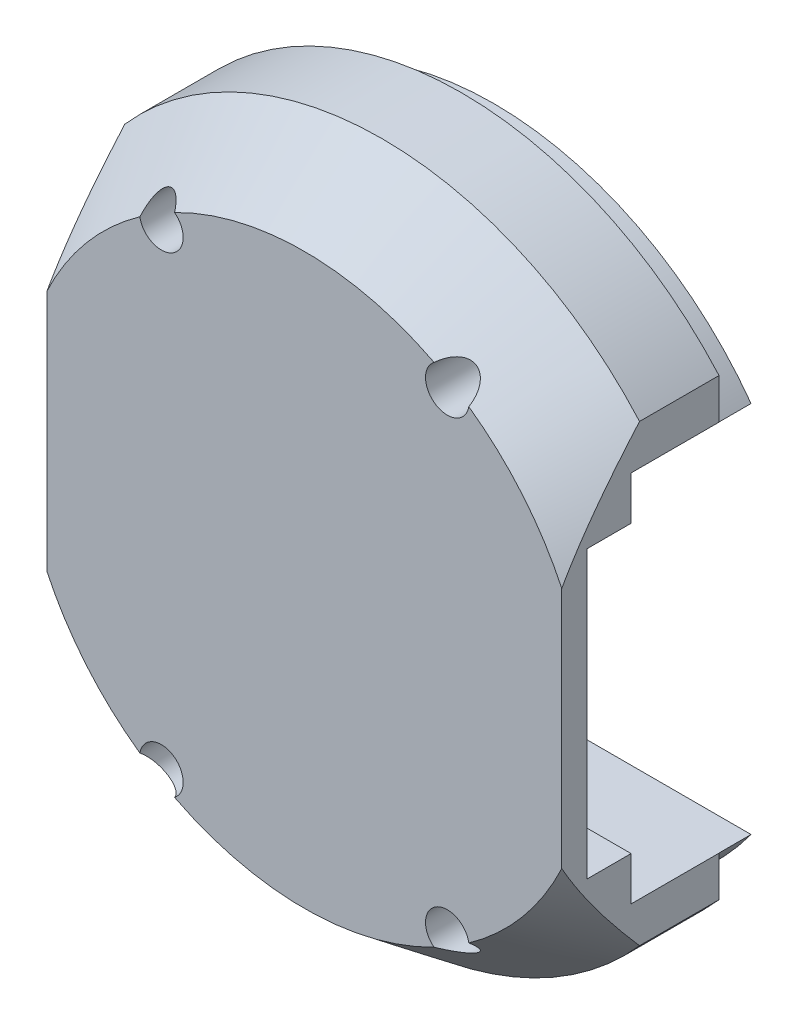
SolidWorks part; units mm, degrees
ref_plane "Front Plane" through (0, 0, 0) normal (0, 0, 1) x (1, 0, 0)
ref_plane "Top Plane" through (0, 0, 0) normal (0, 1, 0) x (1, 0, 0)
ref_plane "Right Plane" through (0, 0, 0) normal (1, 0, 0) x (0, 0, -1)
sketch "Sketch1" plane through (0, 0, 0) normal (0, 0, 1) x (1, 0, 0)
  line L1 (-18.8872, 0) -> (15.5738, 0) construction
  arc A0 (-22.225, -0.0261) -> (22.225, 0) centre (0, 0) ccw
  arc A1 (-22.225, -0.0261) -> (22.225, 0) centre (0, 0) cw
  dimension "D1" = 44.45
extrude "Extrude1" add sketch "Sketch1" along normal blind 2.25
sketch "Sketch2" plane through (0, 0, 2.25) normal (0, 0, 1) x (1, 0, 0)
  line L1 (-19.1115, 0) -> (18.219, 0) construction
  arc A0 (-23.9999, -0.0783) -> (23.9995, 0.1489) centre (0, 0) ccw
  arc A1 (-23.9999, -0.0783) -> (23.9995, 0.1489) centre (0, 0) cw
  dimension "D1" = 48
extrude "Extrude2" add sketch "Sketch2" along normal blind 11
chamfer "Chamfer1" distance 4.1 angle 53 1 edges at (-24, 0, 13.25)
sketch "Sketch6" plane through (0, 0, 0) normal (0, 0, -1) x (-1, 0, 0)
  line L0 (-30, 13.05) -> (30, 13.05)
  line L1 (-30, -13.05) -> (30, -13.05)
  line L2 (-30, -13.05) -> (-30, 13.05)
  line L3 (-30, 0) -> (30, 0) construction
  line L4 (30, -13.05) -> (30, 13.05)
  dimension "D2" = 30
  dimension "D3" = 30
  dimension "D1" = 13.05
extrude "Cut-Extrude1" cut sketch "Sketch6" against normal blind 8.4
sketch "Sketch9" plane through (0, 0, 0) normal (0, 0, -1) x (-1, 0, 0)
  line L1 (-28, -20) -> (-18, -20)
  line L2 (-28, -20) -> (-28, 20)
  line L3 (-28, 20) -> (-18, 20)
  line L4 (-18, -20) -> (-18, 20)
  line L5 (0, 0) -> (0, -27.3159) construction
  line L6 (18, -20) -> (18, 20)
  line L7 (28, 20) -> (18, 20)
  line L8 (28, -20) -> (28, 20)
  line L9 (28, -20) -> (18, -20)
  line L10 (0, 0) -> (18, 0) construction
  dimension "D1" = 40
  dimension "D2" = 18
  dimension "D3" = 10
extrude "Cut-Extrude3" cut sketch "Sketch9" against normal through all
sketch "Sketch10" plane through (0, 0, 8.4) normal (0, 0, -1) x (-1, 0, 0)
  line L1 (22, 10) -> (-22, 10)
  line L2 (22, 10) -> (22, -10)
  line L3 (22, -10) -> (-22, -10)
  line L4 (-22, 10) -> (-22, -10)
  dimension "D1" = 10
  dimension "D2" = 10
  dimension "D3" = 22
  dimension "D4" = 22
extrude "Cut-Extrude4" cut sketch "Sketch10" against normal blind 3.1
sketch "Sketch11" plane through (0, 0, 13.25) normal (0, 0, 1) x (1, 0, 0)
  circle A0 centre (0, 0) radius 6
  dimension "D1" = 12
extrude "Extrude3" [suppressed] add sketch "Sketch11" along normal blind 4.8
sketch "Sketch12" [suppressed] plane through (0, 0, 19.05) normal (0, 0, 1) x (1, 0, 0)
  circle A0 centre (0, 0) radius 2.275
  dimension "D1" = 4.55
extrude "Cut-Extrude5" [suppressed] cut sketch "Sketch12" against normal through all
chamfer "Chamfer2" [suppressed] distance 4 angle 45
sketch "Sketch13" [suppressed] plane through (0, 0, 14.25) normal (0, 0, 1) x (1, 0, 0)
  line L0 (0, 0) -> (0, 33.8431) construction
  line L1 (0, 0) -> (21.9948, 0) construction
  circle A0 centre (10, 16.5) radius 2.5
  circle A1 centre (-10, 16.5) radius 2.5
  circle A2 centre (-10, -16.5) radius 2.5
  circle A3 centre (10, -16.5) radius 2.5
  dimension "D3" = 5
  dimension "D1" = 10
  dimension "D2" = 16.5
extrude "Cut-Extrude6" [suppressed] cut sketch "Sketch13" against normal blind 5
sketch "Sketch14" [suppressed] plane through (0, 0, 9.25) normal (0, 0, 1) x (1, 0, 0)
  line L0 (0, 0) -> (16.3574, 0) construction
  line L1 (0, 0) -> (0, 20.9629) construction
  circle A0 centre (10, 16.5) radius 1.15
  circle A1 centre (-10, 16.5) radius 1.15
  circle A2 centre (-10, -16.5) radius 1.15
  circle A3 centre (10, -16.5) radius 1.15
  dimension "D1" = 2.3
extrude "Cut-Extrude7" [suppressed] cut sketch "Sketch14" against normal through all
sketch "Sketch15" plane through (0, 0, 0) normal (0, 0, -1) x (-1, 0, 0)
  line L0 (0, 0) -> (22.4929, 0) construction
  line L1 (0, 0) -> (0, 30.0852) construction
  line L2 (6, -13) -> (6, 13)
  line L3 (-6, -13) -> (-6, 13)
  line L4 (0, 0) -> (-14.6849, 0) construction
  arc A0 (6, 13) -> (-6, 13) centre (0, 13) ccw
  arc A1 (6, -13) -> (-6, -13) centre (0, -13) cw
  point P3 (-6, 0)
  point P13 (6, 0)
  dimension "D1" = 13
  dimension "D2" = 6
extrude "Cut-Extrude8" cut sketch "Sketch15" against normal up to surface (11.5 mm away) up to face at (0, 0, 11.5)
sketch "Sketch16" plane through (0, 0, 0) normal (0, 0, -1) x (-1, 0, 0)
  line L0 (0, 0) -> (-26.9468, 0) construction
  line L1 (0, 0) -> (0, -31.7311) construction
  circle A0 centre (-10, -16.5) radius 1.525
  circle A1 centre (10, -16.5) radius 1.525
  circle A2 centre (10, 16.5) radius 1.525
  circle A3 centre (-10, 16.5) radius 1.525
  dimension "D1" = 3.05
  dimension "D2" = 16.5
  dimension "D3" = 10
extrude "Cut-Extrude9" cut sketch "Sketch16" against normal through all
sketch "Sketch17" plane through (0, 0, 13.25) normal (0, 0, 1) x (1, 0, 0)
  circle A0 centre (0, 0) radius 2.275
  dimension "D1" = 4.55
extrude "Cut-Extrude10" [suppressed] cut sketch "Sketch17" against normal through all
sketch "Sketch18" [suppressed] plane through (0, 0, 14.25) normal (0, 0, 1) x (1, 0, 0)
  circle A0 centre (0, 0) radius 2.275 construction
  circle A1 centre (0, 0) radius 2.275
  circle A2 centre (0, 0) radius 3.05
  dimension "D1" = 6.1
extrude "Extrude4" [suppressed] add sketch "Sketch18" along normal blind 0.3
chamfer "Chamfer3" [suppressed] distance 0.7 angle 45
fillet "Fillet1" [suppressed] radius 1.2
sketch "Sketch19" [suppressed] plane through (0, 0, 13) normal (0, 0, -1) x (-1, 0, 0)
  line L1 (4, 7) -> (-4, 7)
  line L2 (4, -7) -> (-4, -7)
  line L3 (-4, 13) -> (-4, -13)
  line L4 (4, -13) -> (4, 13)
  line L6 (0, 0) -> (13.3401, 0) construction
  line L7 (-4, 13) -> (-4, 7)
  line L8 (4, -13) -> (4, -7)
  line L9 (4, 7) -> (4, 13)
  line L10 (-4, -7) -> (-4, -13)
  arc A3 (4, 13) -> (-4, 13) centre (0, 13) ccw
  arc A4 (-4, -13) -> (4, -13) centre (0, -13) ccw
  arc A5 (4, 13) -> (-4, 13) centre (0, 13) ccw
  arc A6 (-4, -13) -> (4, -13) centre (0, -13) ccw
  dimension "D1" = 0
  dimension "D2" = 7
extrude "Cut-Extrude11" [suppressed] cut sketch "Sketch19" against normal through all
sketch "Sketch20" [suppressed] plane through (0, 0, 8.4) normal (0, 0, -1) x (-1, 0, 0)
  line L0 (18, 13.05) -> (3.9997, 13.05) construction
  line L1 (6, 13.05) -> (-6, 13.05)
  line L2 (6, 13.05) -> (6, 10)
  line L3 (6, 10) -> (-6, 10)
  line L4 (-6, 13.05) -> (-6, 10)
  line L5 (-4, 10) -> (-18, 10) construction
  line L6 (4, 13) -> (4, 10) construction
  line L7 (-4, 10) -> (-4, 13) construction
  line L8 (0, 0) -> (10.0865, 0) construction
  line L9 (-6, -13.05) -> (-6, -10)
  line L10 (6, -10) -> (-6, -10)
  line L11 (6, -13.05) -> (6, -10)
  line L12 (6, -13.05) -> (-6, -13.05)
  dimension "D1" = 2
  dimension "D2" = 2
extrude "Extrude8" [suppressed] add sketch "Sketch20" against normal blind 3.1
